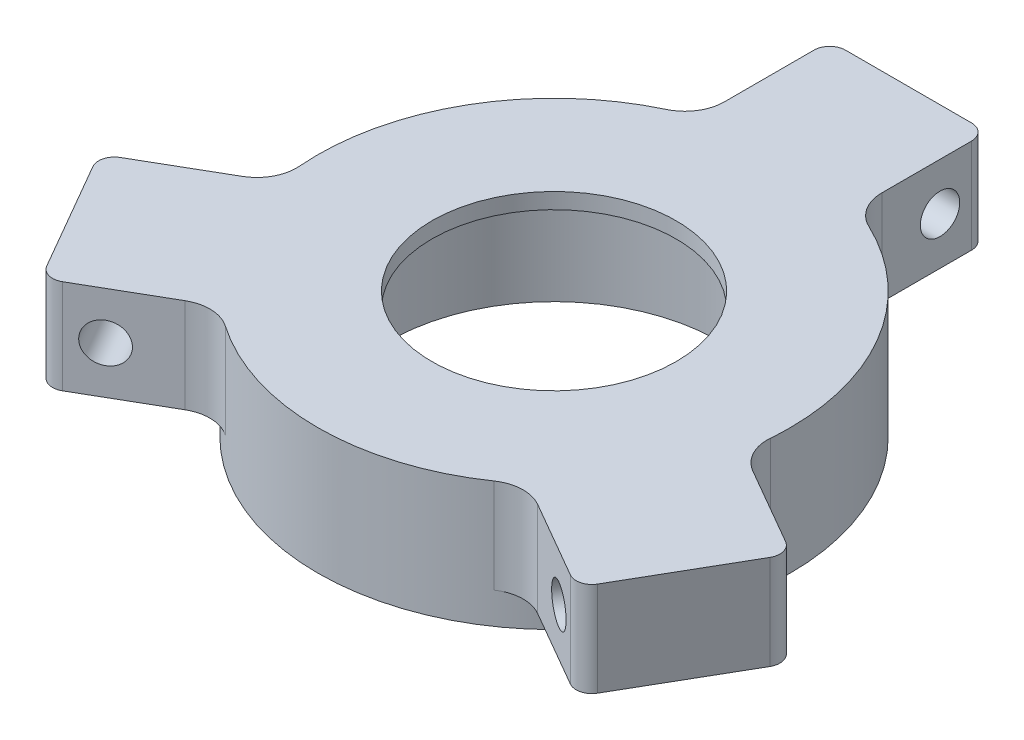
SolidWorks part; units mm, degrees
ref_plane "前视基准面" through (0, 0, 0) normal (0, 0, 1) x (1, 0, 0)
ref_plane "上视基准面" through (0, 0, 0) normal (0, 1, 0) x (1, 0, 0)
ref_plane "右视基准面" through (0, 0, 0) normal (1, 0, 0) x (0, 0, -1)
sketch "草图1" plane through (0, 0, 0) normal (0, 0, 1) x (1, 0, 0)
  line L0 (0, -1000) -> (0, 49000) construction
  line L1 (0, 31.7322) -> (-30, 31.7322)
  line L2 (-30, 31.7322) -> (-30, 11.7322)
  line L4 (-15, -3.2678) -> (0, -3.2678)
  line L5 (0, 31.7322) -> (0, -3.2678)
  line L6 (-30, 11.7322) -> (-30, -3.2678)
  line L7 (-15, -3.2678) -> (-30, -3.2678)
  dimension "D1" = 30
  dimension "D2" = 20
  dimension "D3" = 15
  dimension "D4" = 15
revolve "旋转1" add sketch "草图1" angle 360 about L0
sketch "草图2" plane through (0, 31.7322, 0) normal (0, 1, 0) x (-1, 0, 0)
  line L0 (0, -1000) -> (0, 30) construction
  line L1 (0, 0) -> (34.0667, 19.6684) construction
  line L2 (-19.0414, 10.9936) -> (-36.0374, 20.8062) construction
  line L3 (-33.9711, 31.1603) -> (-19.4949, 22.8024)
  line L5 (-29.4949, 5.4819) -> (-43.9711, 13.8397)
  line L6 (-43.9711, 13.8397) -> (-33.9711, 31.1603)
  line L7 (33.9711, 31.1603) -> (43.9711, 13.8397)
  line L8 (43.9711, 13.8397) -> (29.4949, 5.4819)
  line L10 (19.4949, 22.8024) -> (33.9711, 31.1603)
  line L12 (10, -28.2843) -> (10, -45)
  line L13 (10, -45) -> (-10, -45)
  line L14 (-10, -45) -> (-10, -28.2843)
  arc A0 (-19.4949, 22.8024) -> (-29.4949, 5.4819) centre (0, 0) ccw
  arc A1 (29.4949, 5.4819) -> (19.4949, 22.8024) centre (0, 0) ccw
  arc A2 (-10, -28.2843) -> (10, -28.2843) centre (0, 0) ccw
  dimension "D1" = 120
  dimension "D2" = 120
  dimension "D3" = 20
  dimension "D4" = 20
  dimension "D5" = 20
  dimension "D6" = 10
  dimension "D7" = 10
  dimension "D8" = 10
  dimension "D9" = 45
  dimension "D10" = 45
  dimension "D11" = 45
extrude "拉伸1" add sketch "草图2" against normal blind 12
hole_wizard "M5 螺纹孔1" positions "3D草图1" profile "草图4" tap size "M5" standard "ISO"
sketch3d "3D草图1"
  line L0 (10, 19.7322, -45) -> (10, 31.7322, -45) construction
  line L1 (10, 19.7322, -28.2843) -> (10, 19.7322, -45) construction
  point P0 (10, 25.7322, -39)
  dimension "D1" = 6
  dimension "D2" = 6
sketch "草图4" plane through (10, 25.7322, -39) normal (0, 1, 0) x (0, 0, -1)
  line L0 (0, 0) -> (0, 13.6618)
  line L1 (0, 13.6618) -> (2.1, 12.4)
  line L2 (2.1, 12.4) -> (2.1, 10)
  line L3 (2.1, 10) -> (2.5, 10)
  line L4 (2.5, 10) -> (2.5, 0)
  line L5 (2.5, 0) -> (0, 0)
  line L10 (0, 13.6618) -> (-2.1, 12.4) construction
  line L11 (0, -6.35) -> (0, 107.95) construction
  dimension "蹟恇謂郰芛眻噤" = 4.2
  dimension "蹟恇謂郰芛旮僅" = 12.4
  dimension "蹟恇翋眻噤" = 5
  dimension "蹟恇旮僅" = 10
  dimension "絳芛褒僅" = 118
hole_wizard "M5 螺纹孔2" positions "草图6" profile "草图5" tap size "M5" standard "ISO"
sketch "草图6" plane through (-10, 0, 0) normal (-1, 0, 0) x (0, 0, 1)
  line L0 (-45, 19.7322) -> (-45, 31.7322) construction
  line L1 (-45, 31.7322) -> (-28.2843, 31.7322) construction
  point P1 (-39, 25.7322)
  dimension "D1" = 6
  dimension "D2" = 6
sketch "草图5" plane through (-10, 25.7322, -39) normal (0, 1, 0) x (0, 0, 1)
  line L0 (0, 0) -> (0, 13.6618)
  line L1 (0, 13.6618) -> (2.1, 12.4)
  line L2 (2.1, 12.4) -> (2.1, 10)
  line L3 (2.1, 10) -> (2.5, 10)
  line L4 (2.5, 10) -> (2.5, 0)
  line L5 (2.5, 0) -> (0, 0)
  line L10 (0, 13.6618) -> (-2.1, 12.4) construction
  line L11 (0, -6.35) -> (0, 107.95) construction
  dimension "蹟恇謂郰芛眻噤" = 4.2
  dimension "蹟恇謂郰芛旮僅" = 12.4
  dimension "蹟恇翋眻噤" = 5
  dimension "蹟恇旮僅" = 10
  dimension "絳芛褒僅" = 118
hole_wizard "M5 螺纹孔3" positions "3D草图2" profile "草图7" tap size "M5" standard "ISO"
sketch3d "3D草图2"
  line L0 (33.9711, 19.7322, 31.1603) -> (33.9711, 31.7322, 31.1603) construction
  line L1 (19.4949, 19.7322, 22.8024) -> (33.9711, 19.7322, 31.1603) construction
  point P0 (28.775, 25.7322, 28.1603)
  dimension "D1" = 6
  dimension "D2" = 6
sketch "草图7" plane through (28.775, 25.7322, 28.1603) normal (0, 1, 0) x (0.866, 0, 0.5)
  line L0 (0, 0) -> (0, 13.6618)
  line L1 (0, 13.6618) -> (2.1, 12.4)
  line L2 (2.1, 12.4) -> (2.1, 10)
  line L3 (2.1, 10) -> (2.5, 10)
  line L4 (2.5, 10) -> (2.5, 0)
  line L5 (2.5, 0) -> (0, 0)
  line L10 (0, 13.6618) -> (-2.1, 12.4) construction
  line L11 (0, -6.35) -> (0, 107.95) construction
  dimension "蹟恇謂郰芛眻噤" = 4.2
  dimension "蹟恇謂郰芛旮僅" = 12.4
  dimension "蹟恇翋眻噤" = 5
  dimension "蹟恇旮僅" = 10
  dimension "絳芛褒僅" = 118
hole_wizard "M5 螺纹孔4" positions "3D草图3" profile "草图8" tap size "M5" standard "ISO"
sketch3d "3D草图3"
  line L0 (43.9711, 19.7322, 13.8397) -> (43.9711, 31.7322, 13.8397) construction
  line L1 (43.9711, 31.7322, 13.8397) -> (29.4949, 31.7322, 5.4819) construction
  point P0 (38.775, 25.7322, 10.8397)
  dimension "D1" = 6
  dimension "D2" = 6
sketch "草图8" plane through (38.775, 25.7322, 10.8397) normal (0, 1, 0) x (-0.866, 0, -0.5)
  line L0 (0, 0) -> (0, 13.6618)
  line L1 (0, 13.6618) -> (2.1, 12.4)
  line L2 (2.1, 12.4) -> (2.1, 10)
  line L3 (2.1, 10) -> (2.5, 10)
  line L4 (2.5, 10) -> (2.5, 0)
  line L5 (2.5, 0) -> (0, 0)
  line L10 (0, 13.6618) -> (-2.1, 12.4) construction
  line L11 (0, -6.35) -> (0, 107.95) construction
  dimension "蹟恇謂郰芛眻噤" = 4.2
  dimension "蹟恇謂郰芛旮僅" = 12.4
  dimension "蹟恇翋眻噤" = 5
  dimension "蹟恇旮僅" = 10
  dimension "絳芛褒僅" = 118
hole_wizard "M5 螺纹孔5" positions "草图10" profile "草图9" tap size "M5" standard "ISO"
sketch "草图10" plane through (-5, 0, -8.6603) normal (-0.5, 0, -0.866) x (-0.866, 0, 0.5)
  line L0 (45, 19.7322) -> (45, 31.7322) construction
  line L1 (28.2843, 19.7322) -> (45, 19.7322) construction
  point P0 (39, 25.7322)
  dimension "D1" = 6
  dimension "D2" = 6
sketch "草图9" plane through (-38.775, 25.7322, 10.8397) normal (0, 1, 0) x (-0.866, 0, 0.5)
  line L0 (0, 0) -> (0, 13.6618)
  line L1 (0, 13.6618) -> (2.1, 12.4)
  line L2 (2.1, 12.4) -> (2.1, 10)
  line L3 (2.1, 10) -> (2.5, 10)
  line L4 (2.5, 10) -> (2.5, 0)
  line L5 (2.5, 0) -> (0, 0)
  line L10 (0, 13.6618) -> (-2.1, 12.4) construction
  line L11 (0, -6.35) -> (0, 107.95) construction
  dimension "蹟恇謂郰芛眻噤" = 4.2
  dimension "蹟恇謂郰芛旮僅" = 12.4
  dimension "蹟恇翋眻噤" = 5
  dimension "蹟恇旮僅" = 10
  dimension "絳芛褒僅" = 118
hole_wizard "M5 螺纹孔6" positions "3D草图4" profile "草图11" tap size "M5" standard "ISO"
sketch3d "3D草图4"
  line L0 (-33.9711, 19.7322, 31.1603) -> (-33.9711, 31.7322, 31.1603) construction
  line L1 (-33.9711, 19.7322, 31.1603) -> (-19.4949, 19.7322, 22.8024) construction
  point P0 (-28.775, 25.7322, 28.1603)
  dimension "D1" = 6
  dimension "D2" = 6
sketch "草图11" plane through (-28.775, 25.7322, 28.1603) normal (0, 1, 0) x (0.866, 0, -0.5)
  line L0 (0, 0) -> (0, 13.6618)
  line L1 (0, 13.6618) -> (2.1, 12.4)
  line L2 (2.1, 12.4) -> (2.1, 10)
  line L3 (2.1, 10) -> (2.5, 10)
  line L4 (2.5, 10) -> (2.5, 0)
  line L5 (2.5, 0) -> (0, 0)
  line L10 (0, 13.6618) -> (-2.1, 12.4) construction
  line L11 (0, -6.35) -> (0, 107.95) construction
  dimension "蹟恇謂郰芛眻噤" = 4.2
  dimension "蹟恇謂郰芛旮僅" = 12.4
  dimension "蹟恇翋眻噤" = 5
  dimension "蹟恇旮僅" = 10
  dimension "絳芛褒僅" = 118
sketch "草图12" plane through (0, 31.7322, 0) normal (0, 1, 0) x (-1, 0, 0)
  circle A0 centre (0, 0) radius 15.5
  dimension "D1" = 31
extrude "切除-拉伸1" cut sketch "草图12" against normal through all
chamfer "倒角3" distance 2 angle 45 1 edges at (30, -3.2678, 0)
sketch "草图19" plane through (0, -3.2678, 0) normal (0, -1, 0) x (1, 0, 0)
  circle A1 centre (0, 0) radius 39.8971
extrude "切除-拉伸2" cut sketch "草图19" against normal blind 15
sketch "草图20" plane through (0, 11.7322, 0) normal (0, -1, 0) x (1, 0, 0)
  circle A0 centre (0, 0) radius 21
  dimension "D1" = 42
extrude "切除-拉伸3" cut sketch "草图20" against normal blind 16
sketch "草图22" plane through (0, 27.7322, 0) normal (0, -1, 0) x (1, 0, 0)
  circle A0 centre (0, 0) radius 19
  dimension "D1" = 38
extrude "切除-拉伸5" cut sketch "草图22" against normal blind 2
sketch "草图23" plane through (0, 11.7322, 0) normal (0, -1, 0) x (1, 0, 0)
  circle A0 centre (0, 0) radius 30 construction
  circle A1 centre (0, 0) radius 30
extrude "切除-拉伸6" cut sketch "草图23" against normal blind 4
sketch "草图24" plane through (0, 15.7322, 0) normal (0, -1, 0) x (1, 0, 0)
  line L0 (0, -1000) -> (0, 49000) construction
  line L1 (-500, -866.0254) -> (24500, 42435.2448) construction
  line L2 (500, -866.0254) -> (-24500, 42435.2448) construction
  line L3 (-1000, 0) -> (49000, 0) construction
  circle A0 centre (0, 0) radius 25 construction
  dimension "D1" = 50
hole_wizard "M4 螺纹孔1" positions "3D草图5" profile "草图25" tap size "M4" standard "ISO"
sketch3d "3D草图5"
  line L0 (500, 15.7322, -866.0254) -> (-24500, 15.7322, 42435.2448) construction
  line L2 (-500, 15.7322, -866.0254) -> (24500, 15.7322, 42435.2448) construction
  line L3 (-1000, 15.7322, 0) -> (49000, 15.7322, 0) construction
  circle A0 centre (0, 15.7322, 0) radius 25 construction
  point P0 (-12.5, 15.7322, 21.6506)
  point P6 (0, -9.2678, 0)
  point P11 (12.5, 15.7322, 21.6506)
  point P15 (25, 15.7322, 0)
  point P19 (12.5, 15.7322, -21.6506)
  point P21 (-12.5, 15.7322, -21.6506)
  point P23 (-25, 15.7322, 0)
sketch "草图25" plane through (-12.5, 15.7322, 21.6506) normal (1, 0, 0) x (0, 0, -1)
  line L0 (0, 0) -> (0, 11.0914)
  line L1 (0, 11.0914) -> (1.65, 10.1)
  line L2 (1.65, 10.1) -> (1.65, 8)
  line L3 (1.65, 8) -> (2, 8)
  line L4 (2, 8) -> (2, 0)
  line L5 (2, 0) -> (0, 0)
  line L10 (0, 11.0914) -> (-1.65, 10.1) construction
  line L11 (0, -6.35) -> (0, 107.95) construction
  dimension "蹟恇謂郰芛眻噤" = 3.3
  dimension "蹟恇謂郰芛旮僅" = 10.1
  dimension "蹟恇翋眻噤" = 4
  dimension "蹟恇旮僅" = 8
  dimension "絳芛褒僅" = 118
fillet "圆角1" radius 5 6 edges at (19.4949, 25.7322, 22.8024) (-19.4949, 25.7322, 22.8024) (-29.4949, 25.7322, 5.4819) (-10, 25.7322, -28.2843) (10, 25.7322, -28.2843) (29.4949, 25.7322, 5.4819)
fillet "圆角2" radius 2 6 edges at (-43.9711, 25.7322, 13.8397) (-10, 25.7322, -45) (10, 25.7322, -45) (43.9711, 25.7322, 13.8397) (33.9711, 25.7322, 31.1603) (-33.9711, 25.7322, 31.1603)
